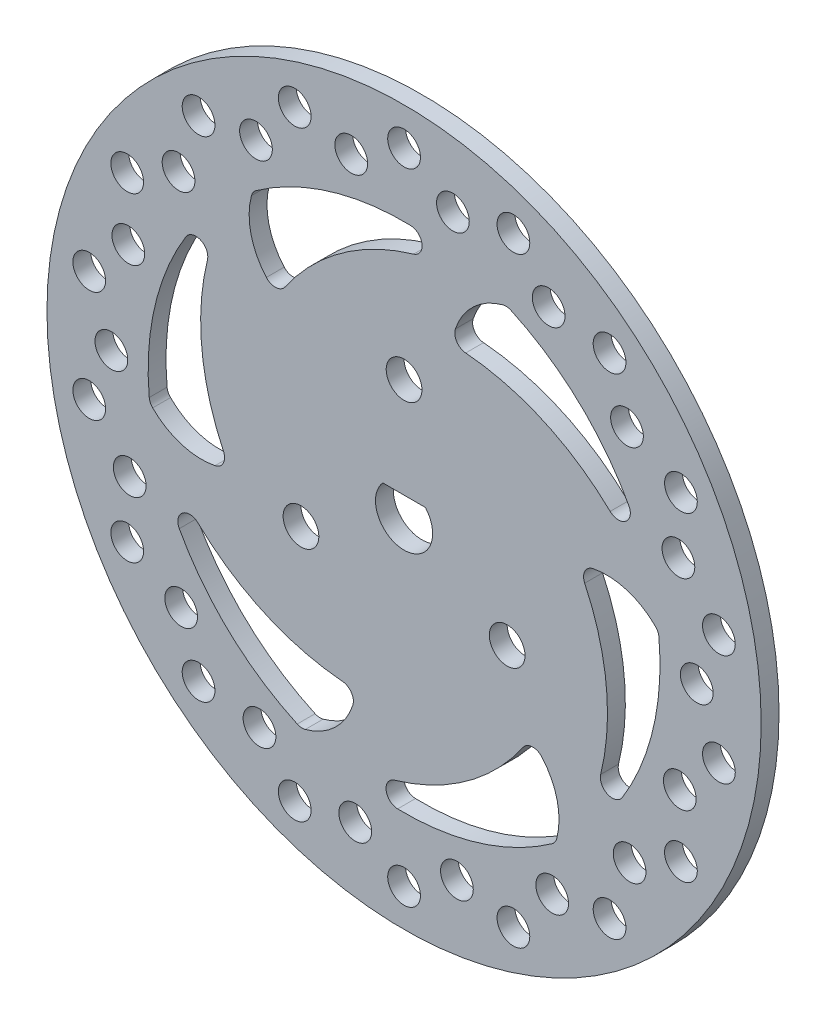
SolidWorks part; units mm, degrees
ref_plane "Front Plane" through (0, 0, 0) normal (0, 0, 1) x (1, 0, 0)
ref_plane "Top Plane" through (0, 0, 0) normal (0, 1, 0) x (1, 0, 0)
ref_plane "Right Plane" through (0, 0, 0) normal (1, 0, 0) x (0, 0, -1)
sketch "Sketch1" plane through (0, 0, 0) normal (0, 0, 1) x (1, 0, 0)
  line L0 (0, -4.8) -> (0, 3.2) construction
  line L1 (-3.5777, 3.2) -> (3.5777, 3.2)
  line L2 (0, 0) -> (0, 53.7108) construction
  line L3 (0, 0) -> (8.2031, 48.4874) construction
  circle A0 centre (0, 0) radius 60
  arc A1 (-36.6855, 22.4316) -> (-42.8144, -3.9907) centre (0, 0) ccw
  circle A3 centre (0, 0) radius 27 construction
  circle A4 centre (0, 20) radius 3
  circle A5 centre (17.3205, -10) radius 3
  circle A6 centre (-17.3205, -10) radius 3
  arc A7 (-3.5777, 3.2) -> (3.5777, 3.2) centre (0, 0) ccw
  arc A14 (-19.994, 23.4978) -> (1.5922, 39.0667) centre (12.6983, 0.919) cw
  arc A18 (8.619, 31.6967) -> (16.5978, 39.188) centre (19.6018, 27.9938) cw
  circle A22 centre (0, 0) radius 20 construction
  arc A23 (10.3527, 29.0643) -> (34.6289, 18.1544) centre (7.145, -10.5375) cw
  arc A24 (31.7596, 8.3841) -> (42.2367, 5.2199) centre (34.0443, -2.9788) cw
  arc A25 (30.3467, 5.5664) -> (33.0366, -20.9123) centre (-5.5533, -11.4565) cw
  arc A26 (23.1406, -23.3126) -> (25.6389, -33.9681) centre (14.4424, -30.9726) cw
  arc A27 (19.994, -23.4978) -> (-1.5922, -39.0667) centre (-12.6983, -0.919) cw
  arc A28 (-8.619, -31.6967) -> (-16.5978, -39.188) centre (-19.6018, -27.9938) cw
  arc A29 (-10.3527, -29.0643) -> (-34.6289, -18.1544) centre (-7.145, 10.5375) cw
  arc A30 (-31.7596, -8.3841) -> (-42.2367, -5.2199) centre (-34.0443, 2.9788) cw
  arc A31 (-30.3467, -5.5664) -> (-33.0366, 20.9123) centre (5.5533, 11.4565) cw
  arc A32 (-23.1406, 23.3126) -> (-25.6389, 33.9681) centre (-14.4424, 30.9726) cw
  arc A33 (1.0836, 42.9863) -> (-24.8633, 35.083) centre (0, 0) ccw
  arc A34 (37.7691, 20.5548) -> (17.9511, 39.0737) centre (0, 0) ccw
  arc A35 (36.6855, -22.4316) -> (42.8144, 3.9907) centre (0, 0) ccw
  arc A36 (-1.0836, -42.9863) -> (24.8633, -35.083) centre (0, 0) ccw
  arc A37 (-37.7691, -20.5548) -> (-17.9511, -39.0737) centre (0, 0) ccw
  arc A38 (-16.5978, -39.188) -> (-17.9511, -39.0737) centre (-17.1162, -37.2564) cw
  arc A39 (-8.619, -31.6967) -> (-10.3527, -29.0643) centre (-10.5142, -31.0577) ccw
  arc A40 (-1.5922, -39.0667) -> (-1.0836, -42.9863) centre (-1.0332, -40.987) ccw
  arc A41 (25.6389, -33.9681) -> (24.8633, -35.083) centre (23.7069, -33.4512) cw
  arc A42 (23.1406, -23.3126) -> (19.994, -23.4978) centre (21.6397, -24.6344) ccw
  arc A43 (33.0366, -20.9123) -> (36.6855, -22.4316) centre (34.9792, -21.3883) ccw
  arc A44 (30.3467, 5.5664) -> (31.7596, 8.3841) centre (32.1539, 6.4233) cw
  arc A45 (42.2367, 5.2199) -> (42.8144, 3.9907) centre (40.823, 3.8051) cw
  arc A46 (34.6289, 18.1544) -> (37.7691, 20.5548) centre (36.0124, 19.5987) ccw
  arc A47 (8.619, 31.6967) -> (10.3527, 29.0643) centre (10.5142, 31.0577) ccw
  arc A48 (16.5978, 39.188) -> (17.9511, 39.0737) centre (17.1162, 37.2564) cw
  arc A49 (1.5922, 39.0667) -> (1.0836, 42.9863) centre (1.0332, 40.987) ccw
  arc A50 (-25.6389, 33.9681) -> (-24.8633, 35.083) centre (-23.7069, 33.4512) cw
  arc A51 (-23.1406, 23.3126) -> (-19.994, 23.4978) centre (-21.6397, 24.6344) ccw
  arc A52 (-33.0366, 20.9123) -> (-36.6855, 22.4316) centre (-34.9792, 21.3883) ccw
  arc A53 (-34.6289, -18.1544) -> (-37.7691, -20.5548) centre (-36.0124, -19.5987) ccw
  arc A54 (-42.2367, -5.2199) -> (-42.8144, -3.9907) centre (-40.823, -3.8051) cw
  arc A55 (-31.7596, -8.3841) -> (-30.3467, -5.5664) centre (-32.1539, -6.4233) ccw
  circle A56 centre (0, 53.7108) radius 2.75
  circle A57 centre (8.2031, 48.4874) radius 2.75
  circle A58 centre (24.292, 42.7577) radius 2.75
  circle A59 centre (18.3702, 50.4716) radius 2.75
  circle A60 centre (37.451, 31.8707) radius 2.75
  circle A61 centre (34.5246, 41.1448) radius 2.75
  circle A62 centre (46.0929, 17.1397) radius 2.75
  circle A63 centre (46.5149, 26.8554) radius 2.75
  circle A64 centre (49.1753, 0.3413) radius 2.75
  circle A65 centre (52.8948, 9.3268) radius 2.75
  circle A66 centre (46.3264, -16.4982) radius 2.75
  circle A67 centre (52.8948, -9.3268) radius 2.75
  circle A68 centre (37.8898, -31.3478) radius 2.75
  circle A69 centre (46.5149, -26.8554) radius 2.75
  circle A70 centre (24.8832, -42.4164) radius 2.75
  circle A71 centre (34.5246, -41.1448) radius 2.75
  circle A72 centre (8.8753, -48.3689) radius 2.75
  circle A73 centre (18.3702, -50.4716) radius 2.75
  circle A74 centre (-8.2031, -48.4874) radius 2.75
  circle A75 centre (0, -53.7108) radius 2.75
  circle A76 centre (-24.292, -42.7577) radius 2.75
  circle A77 centre (-18.3702, -50.4716) radius 2.75
  circle A78 centre (-37.451, -31.8707) radius 2.75
  circle A79 centre (-34.5246, -41.1448) radius 2.75
  circle A80 centre (-46.0929, -17.1397) radius 2.75
  circle A81 centre (-46.5149, -26.8554) radius 2.75
  circle A82 centre (-49.1753, -0.3413) radius 2.75
  circle A83 centre (-52.8948, -9.3268) radius 2.75
  circle A84 centre (-46.3264, 16.4982) radius 2.75
  circle A85 centre (-52.8948, 9.3268) radius 2.75
  circle A86 centre (-37.8898, 31.3478) radius 2.75
  circle A87 centre (-46.5149, 26.8554) radius 2.75
  circle A88 centre (-24.8832, 42.4164) radius 2.75
  circle A89 centre (-34.5246, 41.1448) radius 2.75
  circle A90 centre (-8.8753, 48.3689) radius 2.75
  circle A91 centre (-18.3702, 50.4716) radius 2.75
  point P16 (0, 0)
  point P21 (0, 3.2)
  point P28 (0, 0)
  point P58 (0, 0)
  point P74 (14.0896, 40.6261)
  point P162 (0, 0)
  dimension "D1" = 120
  dimension "D2" = 86
  dimension "D3" = 54
  dimension "D4" = 6
  dimension "D5" = 2
  dimension "D6" = 5.5
  dimension "D7" = 5.5
  dimension "D8" = 18
extrude "Boss-Extrude1" add sketch "Sketch1" along normal blind 3
